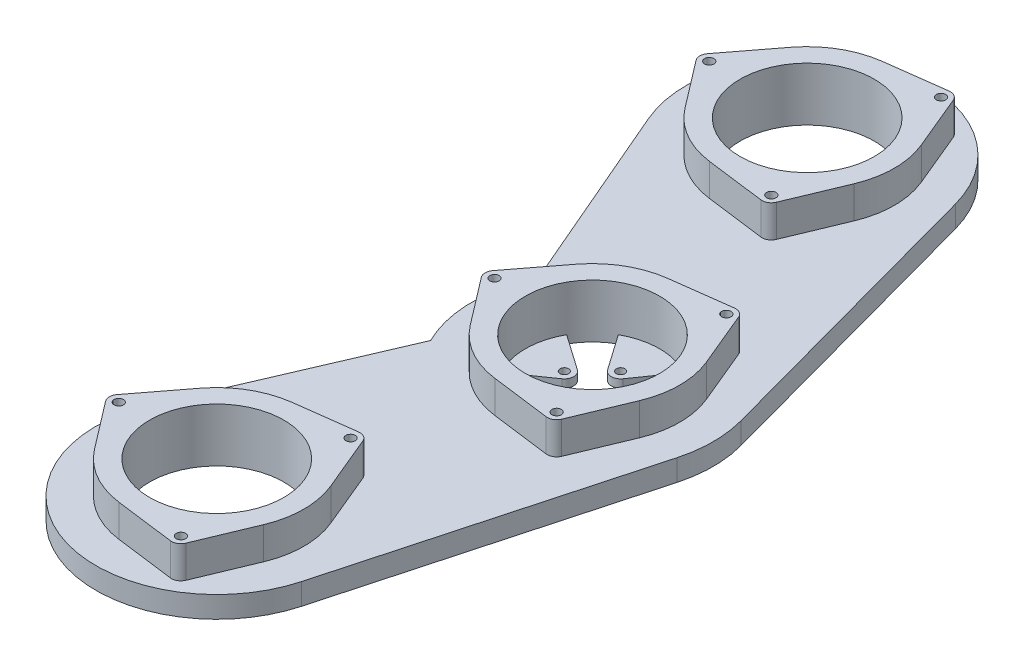
SolidWorks part; units mm, degrees
ref_plane "Alzado" through (0, 0, 0) normal (0, 0, 1) x (1, 0, 0)
ref_plane "Planta" through (0, 0, 0) normal (0, 1, 0) x (1, 0, 0)
ref_plane "Vista lateral" through (0, 0, 0) normal (1, 0, 0) x (0, 0, -1)
sketch "Croquis5" plane through (0, 0, 0) normal (0, 1, 0) x (1, 0, 0)
  line L0 (0, 176.3184) -> (0, -176.3184) construction
  line L1 (-217.2635, 0) -> (217.2635, 0) construction
  line L2 (13.4144, 121.8403) -> (43.4144, 11.8403)
  line L3 (43.4144, -11.8403) -> (13.4144, -121.8403)
  line L6 (-71.3458, 92.237) -> (-40.3113, 20)
  line L7 (-71.3458, -92.237) -> (-40.3113, -20)
  circle A0 centre (0, 0) radius 45
  circle A1 centre (-30, 110) radius 45
  circle A2 centre (-30, -110) radius 45
  point P6 (0, 0)
  point P9 (0, 0)
  dimension "D1" = 90
  dimension "D2" = 220
  dimension "D3" = 30
  dimension "D4" = 20
sketch "Croquis1" plane through (0, 0, 0) normal (0, 1, 0) x (1, 0, 0)
  line L16 (-71.3458, 92.237) -> (-40.3113, 20) construction
  line L17 (-71.3458, -92.237) -> (-40.3113, -20) construction
  line L18 (43.4144, -11.8403) -> (13.4144, -121.8403) construction
  line L19 (13.4144, 121.8403) -> (43.4144, 11.8403) construction
  line L20 (-71.3458, 92.237) -> (-40.3113, 20)
  line L21 (-71.3458, -92.237) -> (-40.3113, -20)
  line L22 (43.4144, -11.8403) -> (13.4144, -121.8403)
  line L23 (13.4144, 121.8403) -> (43.4144, 11.8403)
  circle A10 centre (-30, -110) radius 45 construction
  circle A11 centre (0, 0) radius 45 construction
  circle A12 centre (-30, 110) radius 45 construction
  arc A13 (-71.3458, -92.237) -> (13.4144, -121.8403) centre (-30, -110) ccw
  arc A14 (-40.3113, 20) -> (-40.3113, -20) centre (0, 0) ccw
  arc A15 (13.4144, 121.8403) -> (-71.3458, 92.237) centre (-30, 110) ccw
  arc A16 (43.4144, -11.8403) -> (43.4144, 11.8403) centre (0, 0) ccw
extrude "Saliente-Extruir1" add sketch "Croquis1" along normal blind 8
sketch "Croquis6" plane through (0, 8, 0) normal (0, 1, 0) x (1, 0, 0)
  line L2 (0, 0) -> (-32.5, 0) construction
  line L22 (-39.2808, 2.1253) -> (-25.8219, 19.7352)
  line L23 (-39.2808, -2.1253) -> (-25.8219, -19.7352)
  line L24 (21.481, 32.9555) -> (30.0022, 12.4948)
  line L25 (17.7998, 35.0809) -> (-4.1802, 32.23)
  line L26 (17.7998, -35.0809) -> (-4.1802, -32.23)
  line L27 (21.481, -32.9555) -> (30.0022, -12.4948)
  line L28 (0, 0) -> (-25.8219, 19.7352) construction
  line L33 (-69.2808, -107.8747) -> (-55.8219, -90.2648)
  line L36 (-8.519, -142.9555) -> (0.0022, -122.4948)
  line L40 (-69.2808, -112.1253) -> (-55.8219, -129.7352)
  line L42 (-30, -110) -> (-62.5, -110) construction
  line L45 (-30, -110) -> (-55.8219, -90.2648) construction
  line L46 (-12.2002, -74.9191) -> (-34.1802, -77.77)
  line L47 (-12.2002, -145.0809) -> (-34.1802, -142.23)
  line L48 (-8.519, -77.0445) -> (0.0022, -97.5052)
  line L49 (-69.2808, 107.8747) -> (-55.8219, 90.2648)
  line L50 (-12.2002, 145.0809) -> (-34.1802, 142.23)
  line L51 (-30, 110) -> (-55.8219, 129.7352) construction
  line L52 (-8.519, 142.9555) -> (0.0022, 122.4948)
  line L53 (-30, 110) -> (-62.5, 110) construction
  line L54 (-12.2002, 74.9191) -> (-34.1802, 77.77)
  line L55 (-69.2808, 112.1253) -> (-55.8219, 129.7352)
  line L56 (-8.519, 77.0445) -> (0.0022, 97.5052)
  arc A25 (-25.8219, -19.7352) -> (-4.1802, -32.23) centre (0, 0) ccw
  arc A26 (-39.2808, 2.1253) -> (-39.2808, -2.1253) centre (-36.5, 0) ccw
  arc A27 (21.481, 32.9555) -> (17.7998, 35.0809) centre (18.25, 31.6099) ccw
  arc A28 (17.7998, -35.0809) -> (21.481, -32.9555) centre (18.25, -31.6099) ccw
  arc A29 (-4.1802, 32.23) -> (-25.8219, 19.7352) centre (0, 0) ccw
  arc A30 (30.0022, -12.4948) -> (30.0022, 12.4948) centre (0, 0) ccw
  arc A43 (-55.8219, -129.7352) -> (-34.1802, -142.23) centre (-30, -110) ccw
  arc A44 (-8.519, -77.0445) -> (-12.2002, -74.9191) centre (-11.75, -78.3901) ccw
  arc A45 (-34.1802, -77.77) -> (-55.8219, -90.2648) centre (-30, -110) ccw
  arc A46 (-69.2808, -107.8747) -> (-69.2808, -112.1253) centre (-66.5, -110) ccw
  arc A47 (0.0022, -122.4948) -> (0.0022, -97.5052) centre (-30, -110) ccw
  arc A48 (-12.2002, -145.0809) -> (-8.519, -142.9555) centre (-11.75, -141.6099) ccw
  arc A49 (-34.1802, 142.23) -> (-55.8219, 129.7352) centre (-30, 110) ccw
  arc A50 (-12.2002, 74.9191) -> (-8.519, 77.0445) centre (-11.75, 78.3901) ccw
  arc A51 (-69.2808, 112.1253) -> (-69.2808, 107.8747) centre (-66.5, 110) ccw
  arc A52 (-55.8219, 90.2648) -> (-34.1802, 77.77) centre (-30, 110) ccw
  arc A53 (-8.519, 142.9555) -> (-12.2002, 145.0809) centre (-11.75, 141.6099) ccw
  arc A54 (0.0022, 97.5052) -> (0.0022, 122.4948) centre (-30, 110) ccw
  dimension "D1" = 32.5
  dimension "D2" = 7
  dimension "D3" = 4
  dimension "D5" = 32.5
  dimension "D6" = 7
  dimension "D4" = 3
  dimension "D9" = 32.5
  dimension "D10" = 7
  dimension "D7" = 32.5
  dimension "D8" = 4
  dimension "D11" = 32.5
  dimension "D12" = 4
  dimension "D13" = 32.5
extrude "Saliente-Extruir2" add sketch "Croquis6" along normal blind 12
sketch "Croquis7" plane through (0, 8, 0) normal (0, 1, 0) x (1, 0, 0)
  circle A26 centre (0, 0) radius 25
  circle A27 centre (-30, 110) radius 25
  circle A28 centre (-30, -110) radius 25
  circle A29 centre (-36.5, 0) radius 1.75
  circle A30 centre (18.25, -31.6099) radius 1.75
  circle A31 centre (18.25, 31.6099) radius 1.75
  circle A32 centre (-11.75, 141.6099) radius 1.75
  circle A33 centre (-66.5, 110) radius 1.75
  circle A34 centre (-11.75, 78.3901) radius 1.75
  circle A35 centre (-66.5, -110) radius 1.75
  circle A36 centre (-11.75, -141.6099) radius 1.75
  circle A37 centre (-11.75, -78.3901) radius 1.75
  dimension "D1" = 50
  dimension "D2" = 3.5
extrude "Cortar-Extruir3" cut sketch "Croquis7" against normal through all both and the other way through all
sketch "Croquis8" plane through (0, 0, 0) normal (0, -1, 0) x (1, 0, 0)
  line L0 (0, 0) -> (0, 10.5) construction
  line L1 (0, 10.5) -> (0, 0) construction
  circle A0 centre (0, 0) radius 10.5 construction
  circle A1 centre (0, 10.5) radius 1.6
  circle A2 centre (10.5, 0) radius 1.6
  circle A3 centre (0, -10.5) radius 1.6
  circle A4 centre (-10.5, 0) radius 1.6
  point P14 (0, 0)
  dimension "D1" = 3.2
  dimension "D3" = 0
  dimension "D4" = 21
  dimension "D2" = 4
sketch "Croquis9" plane through (0, 0, 0) normal (0, -1, 0) x (1, 0, 0)
  line L0 (-2.867, 8.4925) -> (-12.1999, 21.8212)
  line L1 (2.867, 8.4925) -> (12.1999, 21.8212)
  line L2 (0, 10.5) -> (0, 19.0199) construction
  line L3 (8.4925, 2.867) -> (21.8212, 12.1999)
  line L4 (8.4925, -2.867) -> (21.8212, -12.1999)
  line L5 (2.867, -8.4925) -> (12.1999, -21.8212)
  line L6 (-2.867, -8.4925) -> (-12.1999, -21.8212)
  line L7 (-8.4925, -2.867) -> (-21.8212, -12.1999)
  line L8 (-8.4925, 2.867) -> (-21.8212, 12.1999)
  arc A0 (-2.867, 8.4925) -> (2.867, 8.4925) centre (0, 10.5) ccw
  circle A1 centre (0, 0) radius 25 construction
  arc A2 (-21.8212, 12.1999) -> (-21.8212, -12.1999) centre (0, 0) ccw
  arc A3 (8.4925, 2.867) -> (8.4925, -2.867) centre (10.5, 0) ccw
  arc A4 (2.867, -8.4925) -> (-2.867, -8.4925) centre (0, -10.5) ccw
  arc A5 (-8.4925, -2.867) -> (-8.4925, 2.867) centre (-10.5, 0) ccw
  arc A6 (12.1999, 21.8212) -> (-12.1999, 21.8212) centre (0, 0) ccw
  arc A7 (21.8212, -12.1999) -> (21.8212, 12.1999) centre (0, 0) ccw
  arc A8 (-12.1999, -21.8212) -> (12.1999, -21.8212) centre (0, 0) ccw
  point P29 (0, 0)
  dimension "D1" = 7
  dimension "D2" = 70
  dimension "D3" = 4
extrude "Saliente-Extruir4" add sketch "Croquis9" against normal blind 3
sketch "Croquis10" plane through (0, 8, 0) normal (0, 1, 0) x (1, 0, 0)
  circle A0 centre (-10.5, 0) radius 1.6 construction
  circle A1 centre (0, -10.5) radius 1.6 construction
  circle A2 centre (10.5, 0) radius 1.6 construction
  circle A3 centre (0, 10.5) radius 1.6 construction
  circle A4 centre (-10.5, 0) radius 1.6
  circle A5 centre (0, -10.5) radius 1.6
  circle A6 centre (10.5, 0) radius 1.6
  circle A7 centre (0, 10.5) radius 1.6
extrude "Cortar-Extruir4" cut sketch "Croquis10" against normal through all
